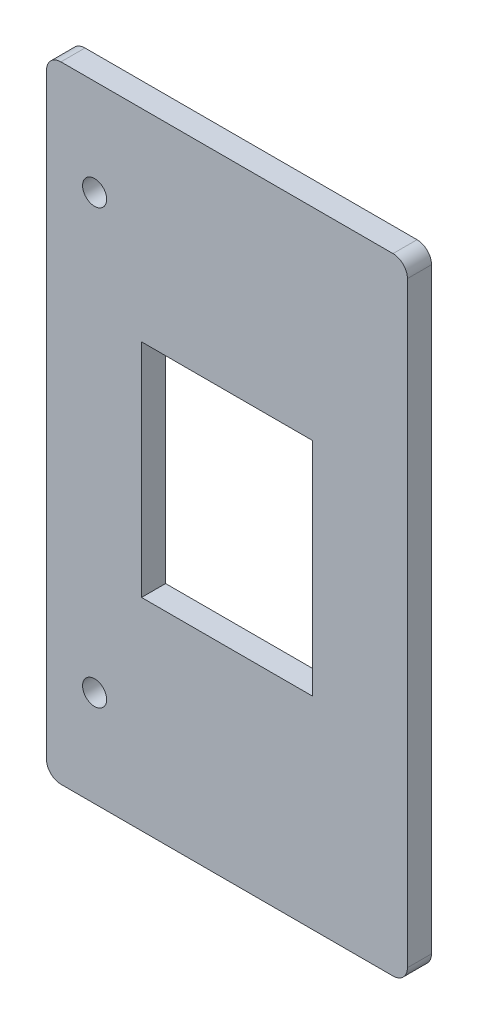
SolidWorks part; units mm, degrees
ref_plane "前视基准面" through (0, 0, 0) normal (0, 0, 1) x (1, 0, 0)
ref_plane "上视基准面" through (0, 0, 0) normal (0, 1, 0) x (1, 0, 0)
ref_plane "右视基准面" through (0, 0, 0) normal (1, 0, 0) x (0, 0, -1)
sketch "草图1" plane through (0, 0, 0) normal (0, 0, 1) x (1, 0, 0)
  line L1 (-37.5, 65) -> (37.5, 65)
  line L2 (-37.5, 65) -> (-37.5, -65)
  line L3 (-37.5, -65) -> (37.5, -65)
  line L4 (37.5, 65) -> (37.5, -65)
  line L5 (0, -65) -> (0, 65) construction
  line L6 (-37.5, 0) -> (37.5, 0) construction
  point P0 (0, 0)
  dimension "D2" = 75
  dimension "D3" = 130
extrude "凸台-拉伸1" add sketch "草图1" along normal blind 5
sketch "草图2" plane through (0, 0, 5) normal (0, 0, 1) x (1, 0, 0)
  line L0 (6, -23) -> (6, -33)
  line L1 (-17.75, 23) -> (17.75, 23)
  line L2 (-17.75, 23) -> (-17.75, -23)
  line L3 (-17.75, -23) -> (17.75, -23)
  line L4 (17.75, 23) -> (17.75, -23)
  line L5 (0, -23) -> (0, 23) construction
  line L6 (-17.75, 0) -> (17.75, 0) construction
  line L7 (6, -33) -> (-6, -33)
  line L8 (-6, -23) -> (-6, -33)
  line L9 (6, 33) -> (-6, 33)
  line L10 (6, 23) -> (6, 33)
  line L11 (-6, 23) -> (-6, 33)
  line L13 (-37.5, 65) -> (-37.5, -65) construction
  circle A0 centre (-27.5, 45) radius 2.5
  circle A1 centre (-27.5, -45) radius 2.5
  point P0 (0, 0)
  point P12 (0, -33)
  point P17 (-24.3384, -45)
  dimension "D3" = 90
  dimension "D1" = 46
  dimension "D2" = 35.5
  dimension "D4" = 12
  dimension "D5" = 10
  dimension "D6" = 10
extrude "切除-拉伸1" cut sketch "草图2" against normal blind 10 contours L4 L1 L2 L3 | A1 | A0
fillet "圆角1" radius 3 4 edges at (37.5, -65, 2.5) (-37.5, -65, 2.5) (-37.5, 65, 2.5) (37.5, 65, 2.5)
sketch "草图3" plane through (0, 0, 5) normal (0, 0, 1) x (1, 0, 0)
  line L0 (0, 59.6866) -> (0, -58.0807) construction
  line L1 (-32.8321, 0) -> (32.4752, 0) construction
